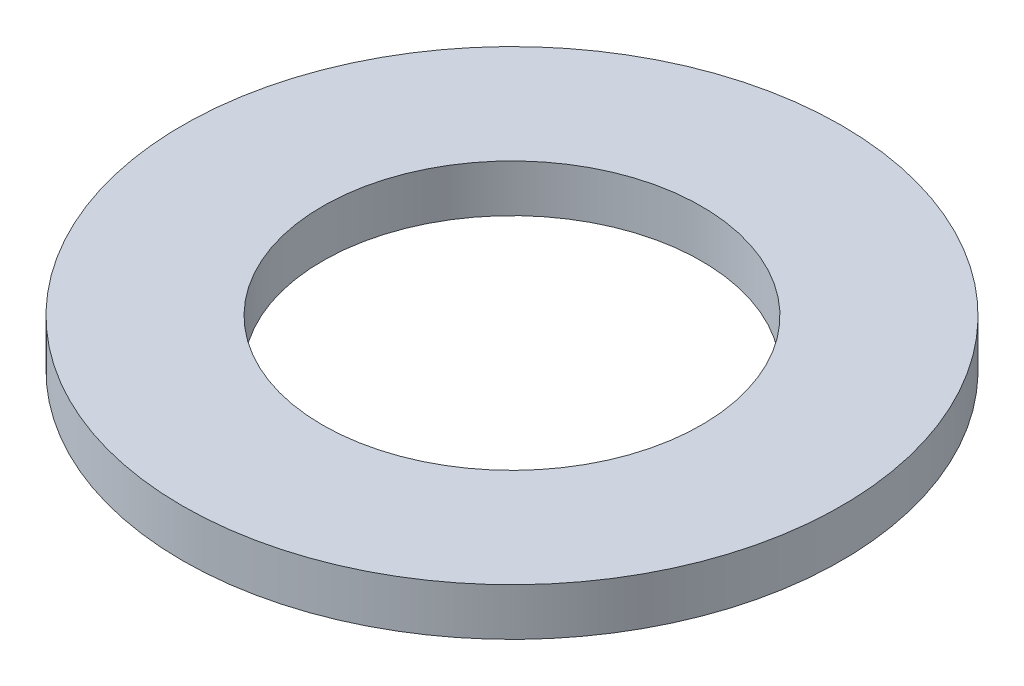
SolidWorks part; units mm, degrees
material "ABS"
ref_plane "前视基准面" through (0, 0, 0) normal (0, 0, 1) x (1, 0, 0)
ref_plane "上视基准面" through (0, 0, 0) normal (0, 1, 0) x (1, 0, 0)
ref_plane "右视基准面" through (0, 0, 0) normal (1, 0, 0) x (0, 0, -1)
other "Configuration Table"
sketch "草图1" plane through (0, 0, 0) normal (0, 1, 0) x (1, 0, 0)
  circle A0 centre (0, 0) radius 4.6
  circle A1 centre (0, 0) radius 8
  dimension "D1" = 9.2
  dimension "D2" = 16
extrude "凸台-拉伸1" add sketch "草图1" along normal blind 1.15
